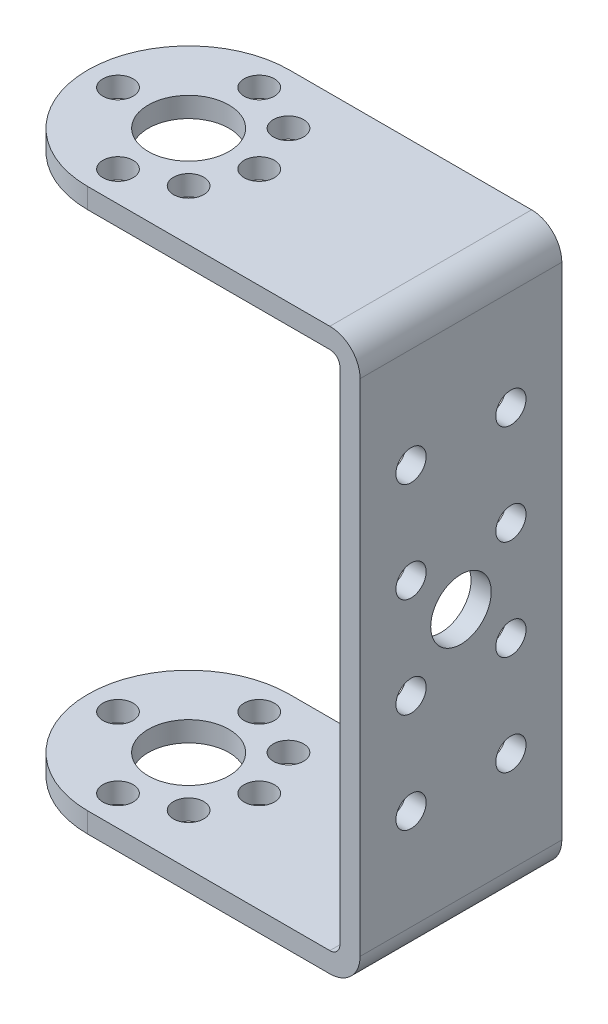
SolidWorks part; units mm, degrees
ref_plane "Front Plane" through (0, 0, 0) normal (0, 0, 1) x (1, 0, 0)
ref_plane "Top Plane" through (0, 0, 0) normal (0, 1, 0) x (1, 0, 0)
ref_plane "Right Plane" through (0, 0, 0) normal (1, 0, 0) x (0, 0, -1)
ref_plane "Plane4" through (0, -27.8, 0) normal (0, -1, 0) x (1, 0, 0)
sketch "Sketch1" plane through (0, -27.8, 0) normal (0, -1, 0) x (1, 0, 0)
  line L0 (0, -10) -> (27, -10)
  line L1 (27, -10) -> (27, 10)
  line L2 (27, 10) -> (0, 10)
  arc A0 (0, 10) -> (0, -10) centre (0, 0) ccw
extrude "Boss-Extrude1" add sketch "Sketch1" against normal blind 55.6
sketch "Sketch2" plane through (0, 0, -10) normal (0, 0, -1) x (-1, 0, 0)
  line L0 (0, 25.8) -> (-25, 25.8)
  line L1 (-25, 25.8) -> (-25, -25.8)
  line L2 (-25, -25.8) -> (0, -25.8)
  line L3 (0, -25.8) -> (0, 25.8)
extrude "Cut-Extrude1" cut sketch "Sketch2" against normal through all
hole_wizard "Ø3.0 (3) Diameter Hole1" positions "Sketch4" profile "Sketch3" hole size "Ø3.0" standard "ANSI Metric"
sketch "Sketch4" plane through (27, 0, 0) normal (1, 0, 0) x (0, 0, -1)
  point P0 (4.9497, 14.8497)
  point P1 (-4.9497, 14.8497)
  point P2 (4.9497, -14.8497)
  point P3 (-4.9497, -14.8497)
sketch "Sketch3" plane through (27, 14.8497, -4.9497) normal (0, 1, 0) x (0, 0, -1)
  line L0 (0, 0) -> (0, 2)
  line L1 (0, 2) -> (1.5, 2)
  line L2 (1.5, 2) -> (1.5, 0)
  line L5 (1.5, 0) -> (0, 0)
  line L11 (0, -6.35) -> (0, 107.95) construction
  dimension "Thru Hole Dia." = 3
  dimension "Thru Hole Depth" = 2
hole_wizard "Ø3.0 (3) Diameter Hole2" positions "Sketch6" profile "Sketch5" hole size "Ø3.0" standard "ANSI Metric"
sketch "Sketch6" plane through (25, 0, 0) normal (-1, 0, 0) x (0, 0, 1)
  point P0 (4.9497, 4.9497)
  point P1 (4.9497, -4.9497)
  point P2 (-4.9497, -4.9497)
  point P3 (-4.9497, 4.9497)
sketch "Sketch5" plane through (25, 4.9497, 4.9497) normal (0, 1, 0) x (0, 0, 1)
  line L0 (0, 0) -> (0, 2)
  line L1 (0, 2) -> (1.5, 2)
  line L2 (1.5, 2) -> (1.5, 0)
  line L5 (1.5, 0) -> (0, 0)
  line L11 (0, -6.35) -> (0, 107.95) construction
  dimension "Thru Hole Dia." = 3
  dimension "Thru Hole Depth" = 2
hole_wizard "Ø6.0 (6) Diameter Hole1" positions "Sketch8" profile "Sketch7" hole size "Ø6.0" standard "ANSI Metric"
sketch "Sketch8" plane through (25, 0, 0) normal (-1, 0, 0) x (0, 0, 1)
  point P0 (0, 0)
sketch "Sketch7" plane through (25, 0, 0) normal (0, 1, 0) x (0, 0, 1)
  line L0 (0, 0) -> (0, 2)
  line L1 (0, 2) -> (3, 2)
  line L2 (3, 2) -> (3, 0)
  line L5 (3, 0) -> (0, 0)
  line L11 (0, -6.35) -> (0, 107.95) construction
  dimension "Thru Hole Dia." = 6
  dimension "Thru Hole Depth" = 2
hole_wizard "Ø3.0 (3) Diameter Hole3" positions "Sketch10" profile "Sketch9" hole size "Ø3.0" standard "ANSI Metric"
sketch "Sketch10" plane through (0, 25.8, 0) normal (0, -1, 0) x (-1, 0, 0)
  point P0 (0, 7)
  point P1 (7, 0)
  point P2 (0, -7)
  point P3 (-7, 0)
  point P4 (-4.9497, 4.9497)
  point P5 (-4.9497, -4.9497)
sketch "Sketch9" plane through (0, 25.8, -7) normal (1, 0, 0) x (0, 0, -1)
  line L0 (0, 0) -> (0, 2)
  line L1 (0, 2) -> (1.5, 2)
  line L2 (1.5, 2) -> (1.5, 0)
  line L5 (1.5, 0) -> (0, 0)
  line L11 (0, -6.35) -> (0, 107.95) construction
  dimension "Thru Hole Dia." = 3
  dimension "Thru Hole Depth" = 2
hole_wizard "Ø8.0 (8) Diameter Hole1" positions "Sketch12" profile "Sketch11" hole size "Ø8.0" standard "ANSI Metric"
sketch "Sketch12" plane through (0, 25.8, 0) normal (0, -1, 0) x (-1, 0, 0)
  point P0 (0, 0)
sketch "Sketch11" plane through (0, 25.8, 0) normal (1, 0, 0) x (0, 0, -1)
  line L0 (0, 0) -> (0, 2)
  line L1 (0, 2) -> (4, 2)
  line L2 (4, 2) -> (4, 0)
  line L5 (4, 0) -> (0, 0)
  line L11 (0, -6.35) -> (0, 107.95) construction
  dimension "Thru Hole Dia." = 8
  dimension "Thru Hole Depth" = 2
hole_wizard "Ø3.0 (3) Diameter Hole4" positions "Sketch14" profile "Sketch13" hole size "Ø3.0" standard "ANSI Metric"
sketch "Sketch14" plane through (0, -27.8, 0) normal (0, -1, 0) x (-1, 0, 0)
  point P0 (0, 7)
  point P1 (7, 0)
  point P2 (0, -7)
  point P3 (-7, 0)
  point P4 (-4.9497, 4.9497)
  point P5 (-4.9497, -4.9497)
sketch "Sketch13" plane through (0, -27.8, -7) normal (1, 0, 0) x (0, 0, -1)
  line L0 (0, 0) -> (0, 2)
  line L1 (0, 2) -> (1.5, 2)
  line L2 (1.5, 2) -> (1.5, 0)
  line L5 (1.5, 0) -> (0, 0)
  line L11 (0, -6.35) -> (0, 107.95) construction
  dimension "Thru Hole Dia." = 3
  dimension "Thru Hole Depth" = 2
hole_wizard "Ø8.0 (8) Diameter Hole2" positions "Sketch16" profile "Sketch15" hole size "Ø8.0" standard "ANSI Metric"
sketch "Sketch16" plane through (0, -27.8, 0) normal (0, -1, 0) x (-1, 0, 0)
  point P0 (0, 0)
sketch "Sketch15" plane through (0, -27.8, 0) normal (1, 0, 0) x (0, 0, -1)
  line L0 (0, 0) -> (0, 2)
  line L1 (0, 2) -> (4, 2)
  line L2 (4, 2) -> (4, 0)
  line L5 (4, 0) -> (0, 0)
  line L11 (0, -6.35) -> (0, 107.95) construction
  dimension "Thru Hole Dia." = 8
  dimension "Thru Hole Depth" = 2
fillet "Fillet1" radius 1 2 edges at (25, 25.8, 0) (25, -25.8, 0)
fillet "Fillet2" radius 3 2 edges at (27, -27.8, 0) (27, 27.8, 0)
sketch "Sketch17" plane through (0, 0, 0) normal (1, 0, 0) x (0, 0, -1)
  line L16 (10, -25.8) -> (10, 25.8)
  line L17 (10, 25.8) -> (8.5, 25.8)
  line L18 (8.5, 25.8) -> (5.5, 25.8)
  line L19 (5.5, 25.8) -> (4, 25.8)
  line L20 (4, 25.8) -> (-4, 25.8)
  line L21 (-4, 25.8) -> (-5.5, 25.8)
  line L22 (-5.5, 25.8) -> (-8.5, 25.8)
  line L23 (-8.5, 25.8) -> (-10, 25.8)
  line L24 (-10, 25.8) -> (-10, -25.8)
  line L25 (-10, -25.8) -> (-8.5, -25.8)
  line L26 (-8.5, -25.8) -> (-5.5, -25.8)
  line L27 (-5.5, -25.8) -> (-4, -25.8)
  line L28 (-4, -25.8) -> (4, -25.8)
  line L29 (4, -25.8) -> (5.5, -25.8)
  line L30 (5.5, -25.8) -> (8.5, -25.8)
  line L31 (8.5, -25.8) -> (10, -25.8)
  line L32 (10, -25.8) -> (10, 25.8)
  line L33 (10, 25.8) -> (8.5, 25.8)
  line L34 (8.5, 25.8) -> (5.5, 25.8)
  line L35 (5.5, 25.8) -> (4, 25.8)
  line L36 (4, 25.8) -> (-4, 25.8)
  line L37 (-4, 25.8) -> (-5.5, 25.8)
  line L38 (-5.5, 25.8) -> (-8.5, 25.8)
  line L39 (-8.5, 25.8) -> (-10, 25.8)
  line L40 (-10, 25.8) -> (-10, -25.8)
  line L41 (-10, -25.8) -> (-8.5, -25.8)
  line L42 (-8.5, -25.8) -> (-5.5, -25.8)
  line L43 (-5.5, -25.8) -> (-4, -25.8)
  line L44 (-4, -25.8) -> (4, -25.8)
  line L45 (4, -25.8) -> (5.5, -25.8)
  line L46 (5.5, -25.8) -> (8.5, -25.8)
  line L47 (8.5, -25.8) -> (10, -25.8)
  dimension "D1" = 0
extrude "Cut-Extrude2" cut sketch "Sketch17" against normal blind 10
